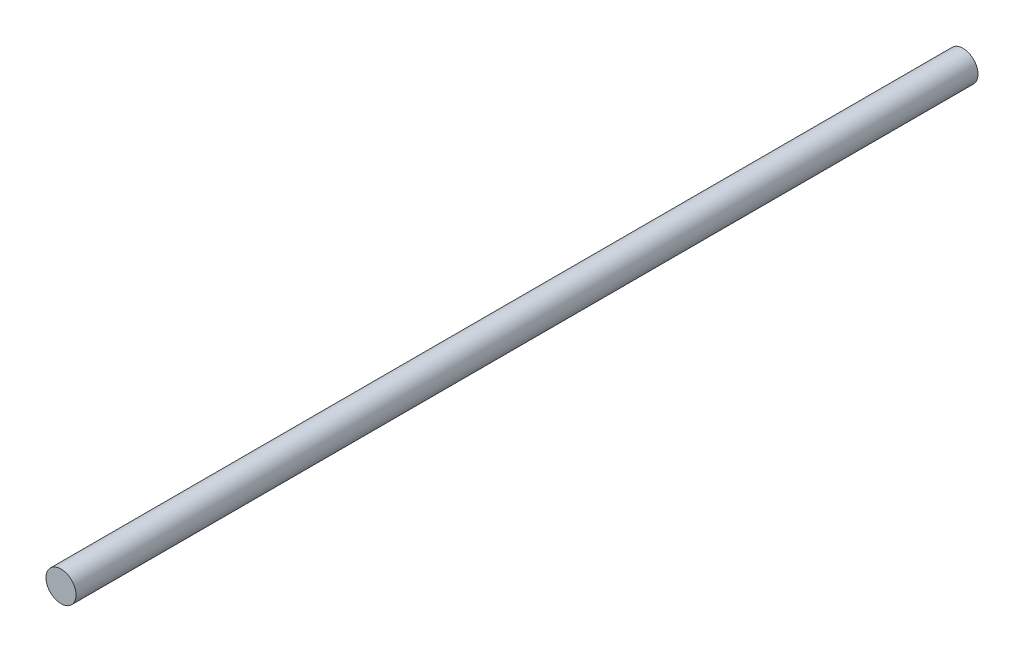
SolidWorks part; units mm, degrees
ref_plane "Plan de face" through (0, 0, 0) normal (0, 0, 1) x (1, 0, 0)
ref_plane "Plan de dessus" through (0, 0, 0) normal (0, 1, 0) x (1, 0, 0)
ref_plane "Plan de droite" through (0, 0, 0) normal (1, 0, 0) x (0, 0, -1)
sketch "Esquisse1" plane through (0, 0, 0) normal (0, 0, 1) x (1, 0, 0)
  circle A0 centre (0, 0) radius 20
  dimension "D1" = 40
extrude "Boss.-Extru.1" add sketch "Esquisse1" along normal blind 1200
